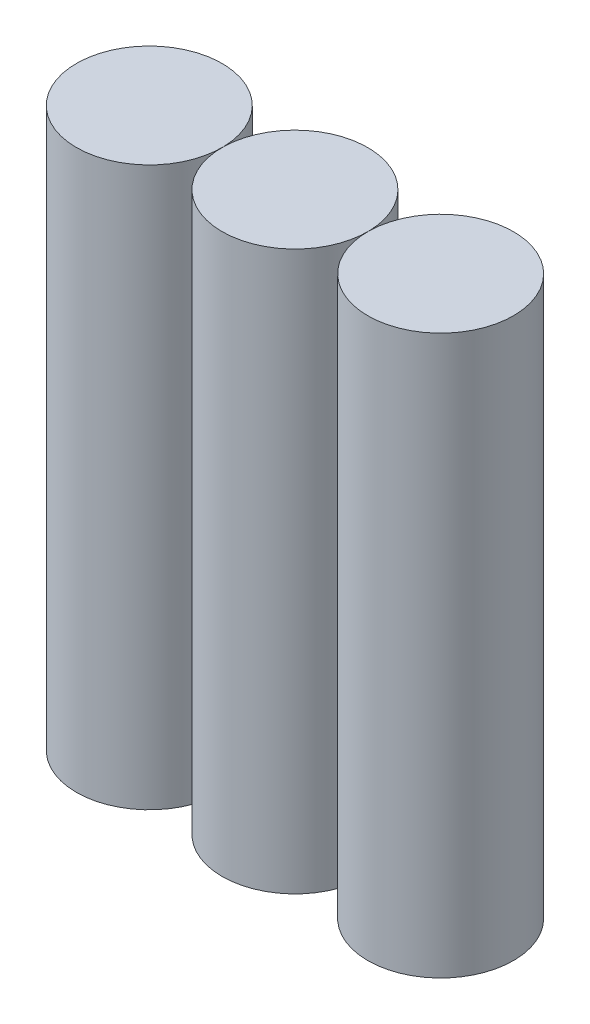
SolidWorks part; units mm, degrees
ref_plane "Front Plane" through (0, 0, 0) normal (0, 0, 1) x (1, 0, 0)
ref_plane "Top Plane" through (0, 0, 0) normal (0, 1, 0) x (1, 0, 0)
ref_plane "Right Plane" through (0, 0, 0) normal (1, 0, 0) x (0, 0, -1)
sketch "Sketch1" plane through (0, 0, 0) normal (0, 1, 0) x (1, 0, 0)
  circle A0 centre (0, 0) radius 9
  circle A1 centre (-18, 0) radius 9
  circle A2 centre (18, 0) radius 9
  point P7 (0, 0)
  point P8 (0, 0)
  point P9 (0, 0)
  dimension "D1" = 18
extrude "Boss-Extrude1" add sketch "Sketch1" along normal mid plane 69 contours A1 | A0 | A2
